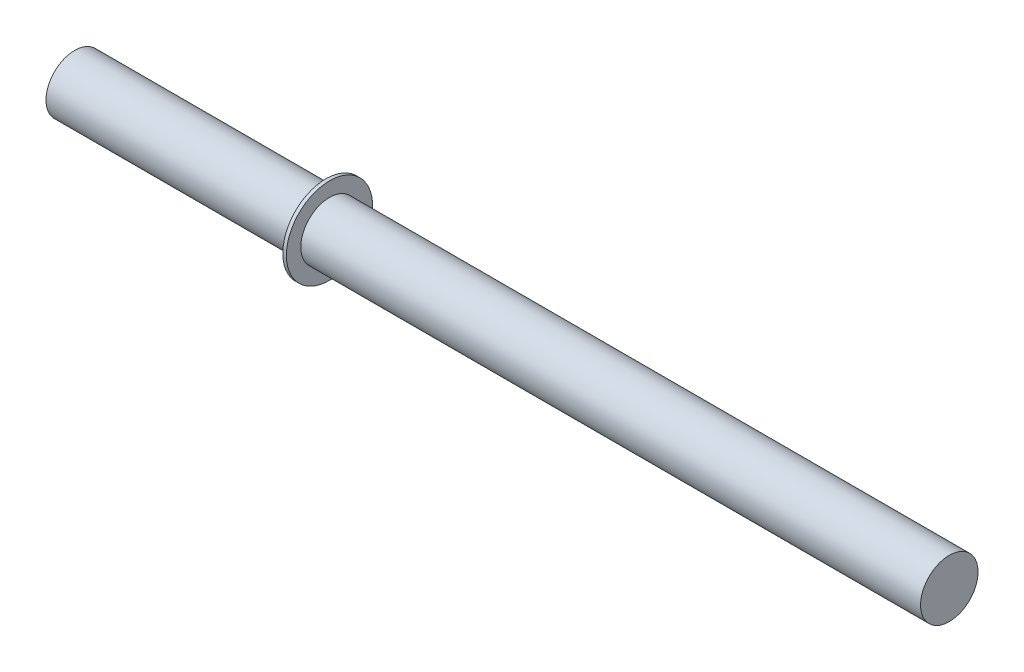
SolidWorks part; units mm, degrees
ref_plane "Plano frontal" through (0, 0, 0) normal (0, 0, 1) x (1, 0, 0)
ref_plane "Plano superior" through (0, 0, 0) normal (0, 1, 0) x (1, 0, 0)
ref_plane "Plano direito" through (0, 0, 0) normal (1, 0, 0) x (0, 0, -1)
sketch "Esboço1" plane through (0, 0, 0) normal (0, 0, 1) x (1, 0, 0)
  line L1 (-60.85, 0) -> (60.85, 0)
  line L2 (-60.85, 0) -> (-60.85, -4)
  line L3 (-60.85, -4) -> (60.85, -4)
  line L4 (60.85, 0) -> (60.85, -4)
  point P4 (0, 0)
  point P5 (0, 0)
revolve "Revolução2" add sketch "Esboço1" angle 360 about L1
sketch "Esboço2" plane through (0, 0, 0) normal (0, 0, 1) x (1, 0, 0)
  line L0 (-25.4, 0) -> (-25.4, -6)
  line L1 (-25.4, -6) -> (-25.9, -6)
  line L2 (-25.9, -6) -> (-25.9, 0)
  line L3 (-25.9, 0) -> (-25.4, 0)
  point P4 (0, 0)
revolve "Revolução3" add sketch "Esboço2" angle 360 about L3
